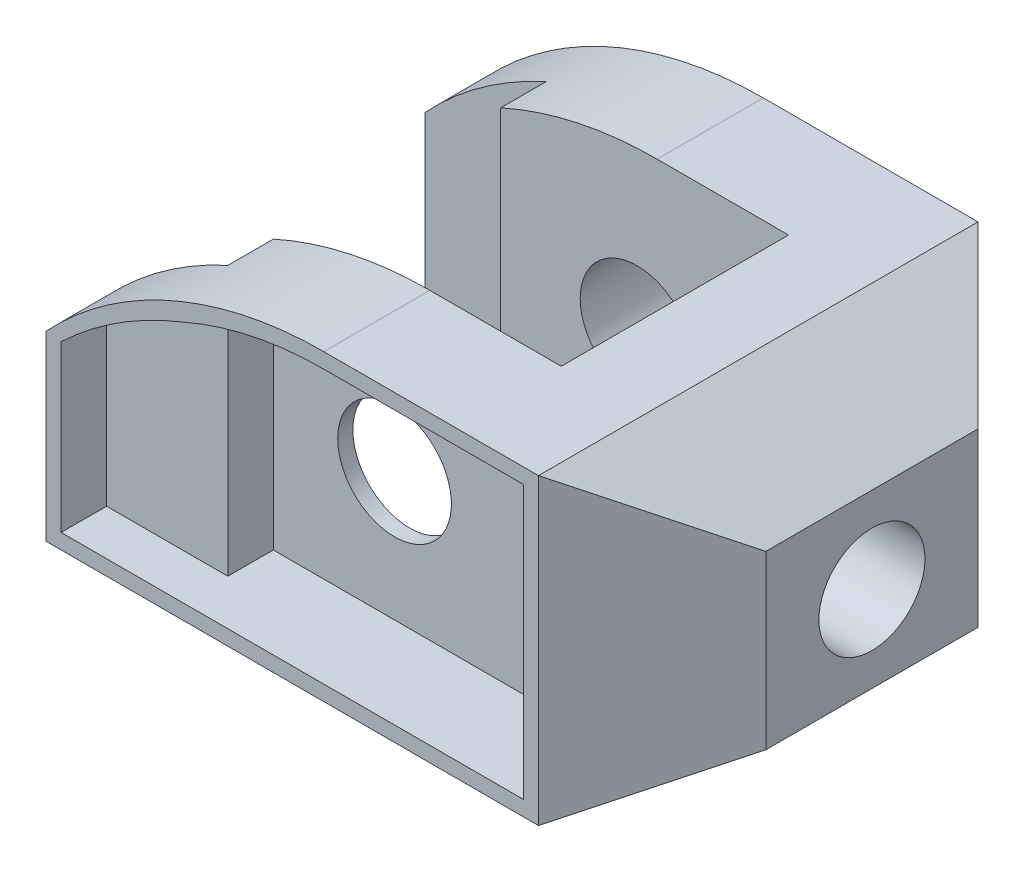
SolidWorks part; units mm, degrees
material "1060 Alloy"
ref_plane "Front Plane" through (0, 0, 0) normal (0, 0, 1) x (1, 0, 0)
ref_plane "Top Plane" through (0, 0, 0) normal (0, 1, 0) x (1, 0, 0)
ref_plane "Right Plane" through (0, 0, 0) normal (1, 0, 0) x (0, 0, -1)
sketch "Sketch1" plane through (0, 0, 0) normal (0, 0, 1) x (1, 0, 0)
  line L0 (0, -20.9292) -> (0, 20.9292) construction
  line L1 (-46, 0) -> (46, 0) construction
  line L2 (-34, 5) -> (-34, -19)
  line L3 (-34, -19) -> (31, -19)
  line L4 (31, -19) -> (46, -10.3397)
  line L5 (46, -10.3397) -> (46, 12.3397)
  line L6 (46, 12.3397) -> (31, 21)
  line L7 (31, 21) -> (2.6606, 21)
  circle A0 centre (0, 0) radius 7.5
  arc A1 (-34, 5) -> (2.6606, 21) centre (2.6606, -29) cw
  point P4 (0, 0)
  point P8 (0, 0)
  dimension "D1" = 15
  dimension "D10" = 50
  dimension "D2" = 24
  dimension "D3" = 65
  dimension "D4" = 40
  dimension "D5" = 19
  dimension "D6" = 31
  dimension "D7" = 15
  dimension "D8" = 30
  dimension "D9" = 30
  dimension "D11" = 21
extrude "Boss-Extrude1" add sketch "Sketch1" along normal blind 58
sketch "Sketch3" plane through (0, -19, 0) normal (0, -1, 0) x (1, 0, 0)
  line L0 (-47.2082, 29) -> (47.2082, 29) construction
  line L1 (-34, 58) -> (31, 58) construction
  line L2 (-34, 58) -> (-34, 50)
  line L3 (-34, 58) -> (-34, 0) construction
  line L4 (-34, 50) -> (-18, 50)
  line L5 (-18, 50) -> (-18, 44)
  line L6 (-18, 44) -> (20, 44)
  line L7 (20, 44) -> (20, 14)
  line L8 (20, 14) -> (-18, 14)
  line L9 (-18, 14) -> (-18, 8)
  line L10 (-18, 8) -> (-34, 8)
  line L11 (-34, 8) -> (-34, 0)
  line L12 (-34, 50) -> (-34, 8)
  point P3 (0, 29)
  line M14 (-34, 58) -> (-34, 0)
  dimension "D1" = 29
  dimension "D2" = 8
  dimension "D3" = 6
  dimension "D4" = 16
  dimension "D5" = 11
  dimension "D6" = 8
  dimension "D7" = 16
  dimension "D8" = 6
extrude "Cut-Extrude1" cut sketch "Sketch3" against normal blind 58 contours L0 L7 L6 L5 L4 M14 | L0 L12 L10 L9 L8 L7
sketch "Sketch4" plane through (0, 0, 0) normal (0, 1, 0) x (1, 0, 0)
  line L0 (31, 0) -> (31, -58)
  line L1 (31, -58) -> (46, -43)
  line L2 (46, -58) -> (46, 0) construction
  line L3 (46, -43) -> (46, -15)
  line L4 (46, -15) -> (31, 0)
  line L5 (46, -58) -> (31, -58) construction
  line L6 (46, 0) -> (31, 0) construction
  line L7 (31, 0) -> (46, 0)
  line L8 (46, 0) -> (46, -15)
  line L9 (31, -58) -> (46, -58)
  line L10 (46, -58) -> (46, -43)
  dimension "D1" = 45
  dimension "D2" = 45
extrude "Cut-Extrude2" cut sketch "Sketch4" against normal blind 58 and the other way blind 58 contours L9 L10 L1 | L8 L7 L4
sketch "Sketch5" plane through (46, 0, 0) normal (1, 0, 0) x (0, 0, -1)
  line L0 (-29, 12.3397) -> (-29, -10.3397) construction
  line L1 (-43, 12.3397) -> (-15, 12.3397) construction
  line L2 (-43, -10.3397) -> (-15, -10.3397) construction
  line L3 (-43, 1) -> (-15, 1) construction
  line L4 (-43, 12.3397) -> (-43, -10.3397) construction
  line L5 (-15, 12.3397) -> (-15, -10.3397) construction
  circle A0 centre (-29, 1) radius 7
  dimension "D1" = 14
extrude "Cut-Extrude3" cut sketch "Sketch5" against normal blind 58
sketch "Sketch6" plane through (0, 0, 58) normal (0, 0, 1) x (1, 0, 0)
  line L0 (-34, -19) -> (31, -19) construction
  line L1 (2.6469, 19) -> (29, 19)
  line L2 (-16, 15.0511) -> (-16, -17)
  line L3 (-16, -17) -> (29, -17)
  line L4 (29, 19) -> (29, -17)
  line L6 (31, 21) -> (2.6606, 21) construction
  line L7 (31, 21) -> (31, -19) construction
  line L9 (-32, 3.2588) -> (-32, -17)
  line L10 (-32, -17) -> (-16, -17)
  line L11 (-34, 5) -> (-34, -19) construction
  circle A0 centre (0, 0) radius 7.5
  arc A1 (2.6469, 19) -> (-32, 3.2588) centre (2.6469, -27) ccw
  arc A2 (2.6606, 21) -> (-34, 5) centre (2.6606, -29) ccw construction
  circle M10 centre (0, 0) radius 7.5
  dimension "D5" = 2
  dimension "D7" = 46
  dimension "D8" = 15
  dimension "D1" = 2
  dimension "D2" = 2
  dimension "D3" = 2
  dimension "D4" = 16
  dimension "D6" = 2
extrude "Cut-Extrude14" cut sketch "Sketch6" against normal blind 12 contours L1 A1 L2 L3 L4 M10 | M10
sketch "Sketch7" plane through (0, 0, 58) normal (0, 0, 1) x (1, 0, 0)
  line L0 (-16, -17) -> (-32, -17)
  line L1 (-32, -17) -> (-32, 4.8022)
  line L2 (-34, 5) -> (-34, -19) construction
  line L3 (-16, 15.0511) -> (-16, -17)
  arc A0 (-16, 15.0511) -> (-32, 4.8022) centre (2.178, -30.9409) ccw
  arc A1 (2.6606, 21) -> (-34, 5) centre (2.6606, -29) ccw construction
  dimension "D2" = 2
  dimension "D3" = 49.4541
  dimension "D1" = 2
extrude "Cut-Extrude15" cut sketch "Sketch7" against normal blind 6
